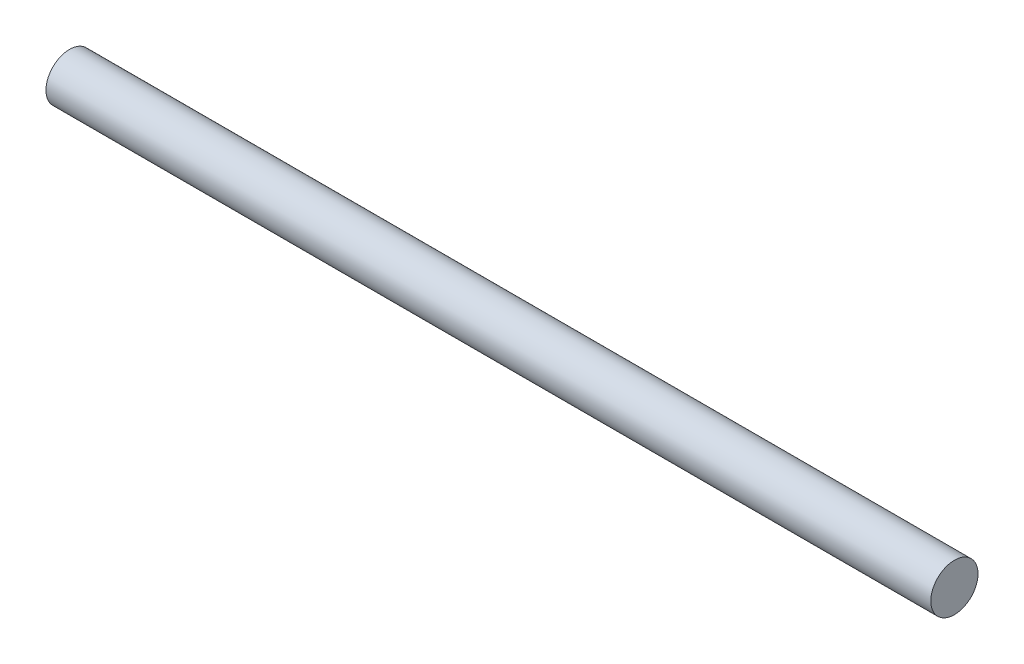
SolidWorks part; units mm, degrees
ref_plane "Front Plane" through (0, 0, 0) normal (0, 0, 1) x (1, 0, 0)
ref_plane "Top Plane" through (0, 0, 0) normal (0, 1, 0) x (1, 0, 0)
ref_plane "Right Plane" through (0, 0, 0) normal (1, 0, 0) x (0, 0, -1)
sketch "Sketch1" plane through (0, 0, 0) normal (1, 0, 0) x (0, 0, -1)
  circle A0 centre (0, 0) radius 4
  dimension "D1" = 8
extrude "Boss-Extrude1" add sketch "Sketch1" along normal blind 150
